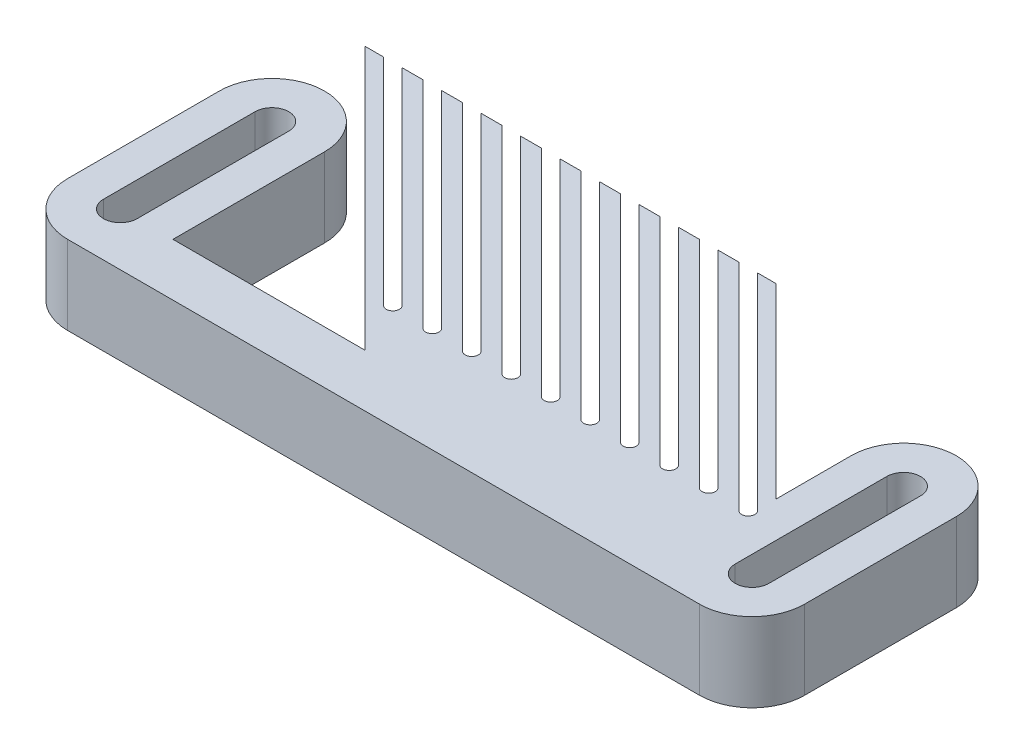
SolidWorks part; units mm, degrees
material "Rubber"
ref_plane "Front Plane" through (0, 0, 0) normal (0, 0, 1) x (1, 0, 0)
ref_plane "Top Plane" through (0, 0, 0) normal (0, 1, 0) x (1, 0, 0)
ref_plane "Right Plane" through (0, 0, 0) normal (1, 0, 0) x (0, 0, -1)
sketch "Sketch1" plane through (0, 0, 0) normal (0, 1, 0) x (1, 0, 0)
  line L1 (-88.9, 38.1) -> (88.9, 38.1)
  line L2 (-88.9, 38.1) -> (-88.9, -38.1)
  line L3 (-88.9, -38.1) -> (88.9, -38.1)
  line L4 (88.9, 38.1) -> (88.9, -38.1)
  line L5 (-88.9, 38.1) -> (88.9, -38.1) construction
  line L6 (-88.9, -38.1) -> (88.9, 38.1) construction
  point P0 (0, 0)
  dimension "D1" = 177.8
  dimension "D2" = 76.2
extrude "Boss-Extrude1" add sketch "Sketch1" along normal blind 19.05
sketch "Sketch2" plane through (0, 19.05, 0) normal (0, 1, 0) x (1, 0, 0)
  line L0 (-76.2, 38.1) -> (-24.2775, -13.8225)
  line L1 (-22.0324, -11.5775) -> (-71.7099, 38.1)
  line L2 (88.9, 38.1) -> (-88.9, 38.1) construction
  line L3 (-71.7099, 38.1) -> (-76.2, 38.1)
  line L4 (-88.9, 38.1) -> (-88.9, -38.1) construction
  arc A0 (-24.2775, -13.8225) -> (-22.0324, -11.5775) centre (-23.1549, -12.7) ccw
  dimension "D1" = 45
  dimension "D2" = 50.8
  dimension "D3" = 3.175
  dimension "D4" = 12.7
extrude "Cut-Extrude1" cut sketch "Sketch2" against normal through all
pattern_linear "LPattern1" count 10 spacing 9.525 along (1, 0, 0) of "Cut-Extrude1"
sketch "Sketch3" plane through (0, 19.05, 0) normal (0, 1, 0) x (1, 0, 0)
  line L0 (-76.2, -7.112) -> (76.2, -7.112) construction
  line L1 (-88.9, 38.1) -> (-88.9, -38.1) construction
  line L2 (-88.9, -38.1) -> (88.9, -38.1) construction
  line L3 (-76.2, 11.176) -> (-76.2, -25.4) construction
  line L4 (-72.136, 11.176) -> (-72.136, -25.4)
  line L5 (-80.264, 11.176) -> (-80.264, -25.4)
  line L6 (76.2, 11.176) -> (76.2, -25.4) construction
  line L7 (80.264, 11.176) -> (80.264, -25.4)
  line L8 (72.136, 11.176) -> (72.136, -25.4)
  line L9 (0, 0) -> (0, -7.112) construction
  arc A0 (-72.136, 11.176) -> (-80.264, 11.176) centre (-76.2, 11.176) ccw
  arc A1 (-80.264, -25.4) -> (-72.136, -25.4) centre (-76.2, -25.4) ccw
  arc A2 (80.264, 11.176) -> (72.136, 11.176) centre (76.2, 11.176) ccw
  arc A3 (72.136, -25.4) -> (80.264, -25.4) centre (76.2, -25.4) ccw
  point P7 (-76.2, -7.112)
  point P13 (76.2, -7.112)
  dimension "D3" = 4.064
  dimension "D1" = 12.7
  dimension "D2" = 36.576
  dimension "D4" = 12.7
sketch "Sketch4" plane through (0, 19.05, 0) normal (0, 1, 0) x (1, 0, 0)
  line L0 (64.1576, -12.7) -> (64.1576, 38.1)
  line L1 (88.9, 38.1) -> (14.0151, 38.1) construction
  line L2 (64.1576, 38.1) -> (14.0151, 38.1)
  line L3 (14.0151, 38.1) -> (64.1576, -12.7)
  arc A0 (61.4475, -13.8225) -> (63.6926, -11.5775) centre (62.5701, -12.7) ccw construction
extrude "Cut-Extrude2" [suppressed] cut sketch "Sketch4" against normal through all
extrude "Cut-Extrude3" cut sketch "Sketch3" against normal through all
fillet "Fillet1" radius 12.7 2 edges at (88.9, 9.525, 38.1) (-88.9, 9.525, 38.1)
sketch "Sketch5" plane through (0, 19.05, 0) normal (0, 1, 0) x (1, 0, 0)
  line L0 (-88.9, 38.1) -> (-88.9, 11.176)
  line L1 (-88.9, 38.1) -> (-88.9, -25.4) construction
  line L2 (-63.5, 11.176) -> (-63.5, -25.4)
  line L3 (-63.5, -25.4) -> (-17.1901, -25.4)
  line L4 (-17.1901, -25.4) -> (-80.6901, 38.1)
  line L5 (-76.2, 38.1) -> (-88.9, 38.1) construction
  line L6 (-80.6901, 38.1) -> (-88.9, 38.1)
  line L7 (88.9, 38.1) -> (88.9, 11.176)
  line L8 (88.9, -25.4) -> (88.9, 38.1) construction
  line L9 (63.5, 11.176) -> (63.5, -6.8947)
  line L10 (63.5, -6.8947) -> (18.5053, 38.1)
  line L11 (88.9, 38.1) -> (14.0151, 38.1) construction
  line L12 (18.5053, 38.1) -> (88.9, 38.1)
  line L13 (-76.2, 38.1) -> (-24.2775, -13.8225) construction
  line L14 (-76.2, -38.1) -> (76.2, -38.1) construction
  line L15 (63.6926, -11.5775) -> (14.0151, 38.1) construction
  arc A0 (-88.9, 11.176) -> (-63.5, 11.176) centre (-76.2, 11.176) cw
  arc A1 (88.9, 11.176) -> (63.5, 11.176) centre (76.2, 11.176) ccw
  arc A2 (-72.136, 11.176) -> (-80.264, 11.176) centre (-76.2, 11.176) ccw construction
  arc A3 (80.264, 11.176) -> (72.136, 11.176) centre (76.2, 11.176) ccw construction
  dimension "D2" = 3.175
  dimension "D1" = 12.7
  dimension "D3" = 3.175
extrude "Cut-Extrude4" cut sketch "Sketch5" against normal up to next
